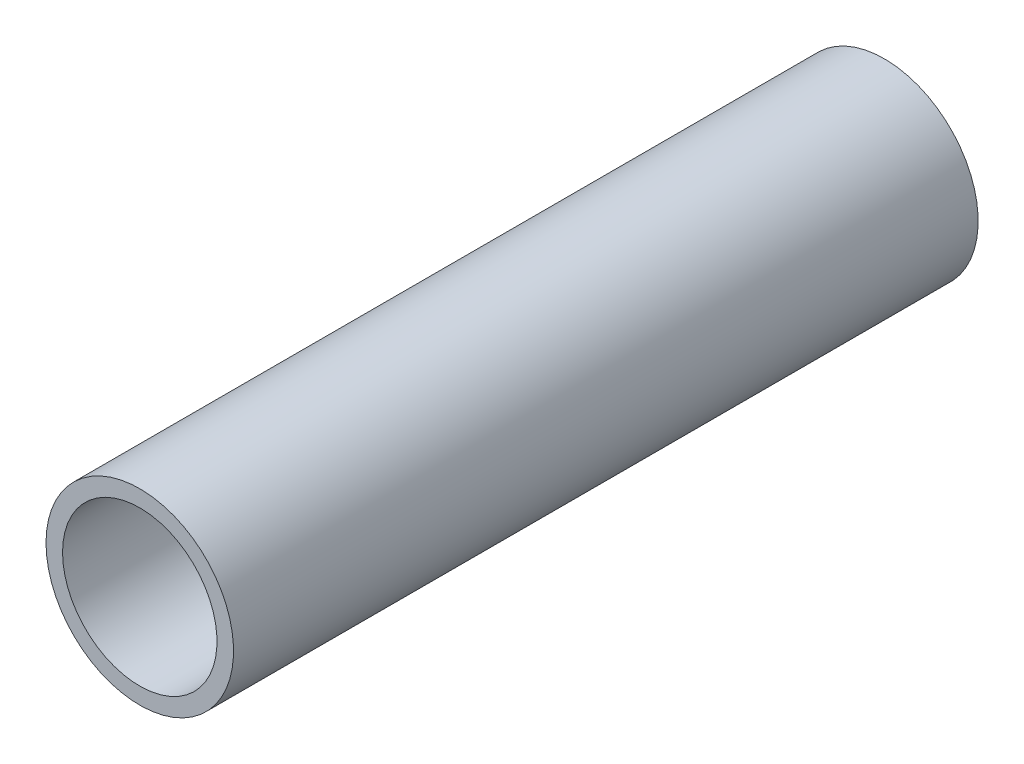
SolidWorks part; units mm, degrees
material "Plain Carbon Steel"
ref_plane "Front Plane" through (0, 0, 0) normal (0, 0, 1) x (1, 0, 0)
ref_plane "Top Plane" through (0, 0, 0) normal (0, 1, 0) x (1, 0, 0)
ref_plane "Right Plane" through (0, 0, 0) normal (1, 0, 0) x (0, 0, -1)
sketch "Sketch1" plane through (0, 0, 0) normal (0, 0, 1) x (1, 0, 0)
  circle A0 centre (351.5, -25) radius 17
  circle A1 centre (351.5, -25) radius 14
  arc A4 (368.5, -25) -> (334.5, -25) centre (351.5, -25) ccw construction
  dimension "D1" = 28
extrude "Boss-Extrude1" add sketch "Sketch1" along normal offset from surface 20 and the other way offset from surface (95 mm away) 10
